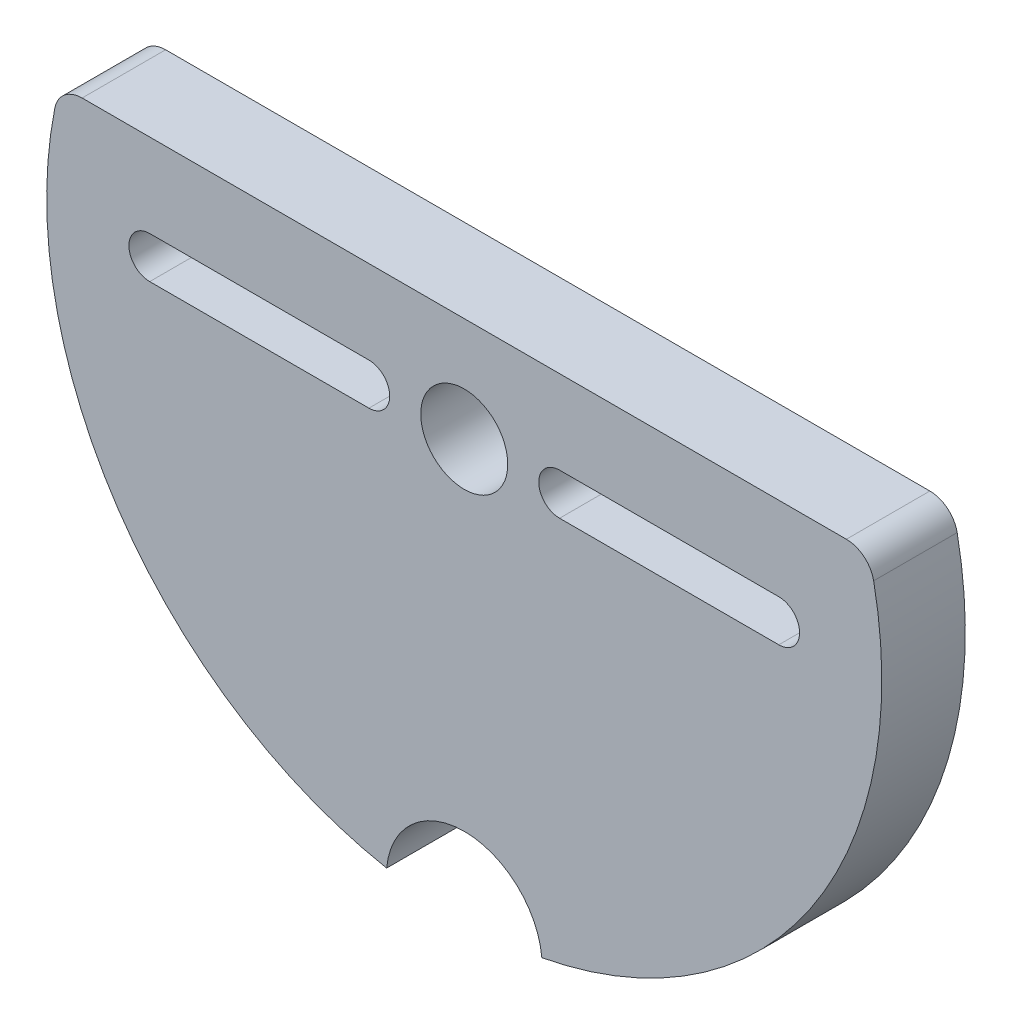
SolidWorks part; units mm, degrees
ref_plane "Front Plane" through (0, 0, 0) normal (0, 0, 1) x (1, 0, 0)
ref_plane "Top Plane" through (0, 0, 0) normal (0, 1, 0) x (1, 0, 0)
ref_plane "Right Plane" through (0, 0, 0) normal (1, 0, 0) x (0, 0, -1)
sketch "Sketch1" plane through (0, 0, 0) normal (0, 0, 1) x (1, 0, 0)
  line L1 (0, 0) -> (0, -19.05) construction
  line L2 (-3.5405, -18.7181) -> (0, -19.05) construction
  line L3 (17.4336, 4.7625) -> (-17.4336, 4.7625)
  arc A1 (-18.6789, 3.742) -> (-3.5405, -18.7181) centre (0, 0) ccw
  arc A2 (-3.5405, -18.7181) -> (3.5405, -18.7181) centre (0, -19.05) cw
  arc A3 (-17.4336, 4.7625) -> (-18.6789, 3.742) centre (-17.4336, 3.4925) ccw
  arc A5 (18.6789, 3.742) -> (3.5405, -18.7181) centre (0, 0) cw
  arc A6 (17.4336, 4.7625) -> (18.6789, 3.742) centre (17.4336, 3.4925) cw
  dimension "D1" = 3.556
  dimension "D3" = 19.05
  dimension "D4" = 1.27
  dimension "D2" = 4.7625
extrude "Boss-Extrude1" add sketch "Sketch1" along normal blind 3.81
sketch "Sketch4" plane through (0, 0, 3.81) normal (0, 0, 1) x (1, 0, 0)
  line L0 (-14.35, 0) -> (-4.35, 0) construction
  line L1 (-14.35, 0.95) -> (-4.35, 0.95)
  line L2 (-14.35, -0.95) -> (-4.35, -0.95)
  line L3 (4.35, 0) -> (14.35, 0) construction
  line L4 (4.35, 0.95) -> (14.35, 0.95)
  line L5 (4.35, -0.95) -> (14.35, -0.95)
  line L6 (-4.35, 0) -> (4.35, 0) construction
  line L7 (-4.35, 0.95) -> (4.35, 0.95) construction
  arc A0 (-14.35, 0.95) -> (-14.35, -0.95) centre (-14.35, 0) ccw
  arc A1 (-4.35, -0.95) -> (-4.35, 0.95) centre (-4.35, 0) ccw
  arc A2 (4.35, 0.95) -> (4.35, -0.95) centre (4.35, 0) ccw
  arc A3 (14.35, -0.95) -> (14.35, 0.95) centre (14.35, 0) ccw
  circle A4 centre (0, 0) radius 1.9844
  point P3 (-9.35, 0)
  point P8 (9.35, 0)
  point P17 (0, 0)
  dimension "D4" = 3.9688
  dimension "D1" = 28.7
  dimension "D2" = 1.9
  dimension "D3" = 8.7
extrude "Cut-Extrude2" cut sketch "Sketch4" against normal through all
